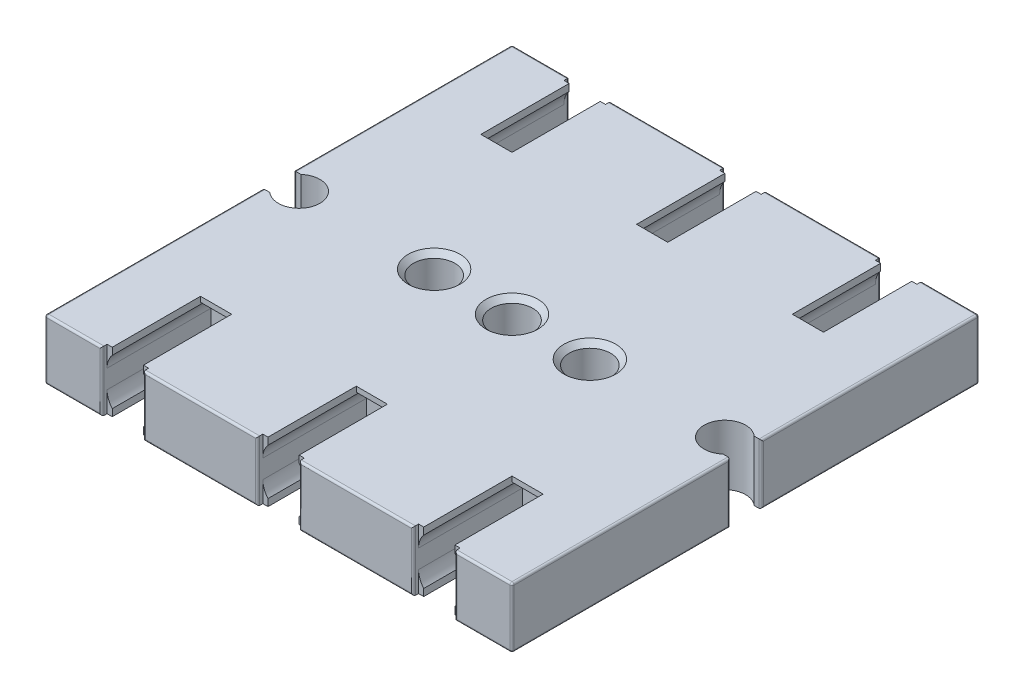
SolidWorks part; units mm, degrees
ref_plane "前视基准面" through (0, 0, 0) normal (0, 0, 1) x (1, 0, 0)
ref_plane "上视基准面" through (0, 0, 0) normal (0, 1, 0) x (1, 0, 0)
ref_plane "右视基准面" through (0, 0, 0) normal (1, 0, 0) x (0, 0, -1)
sketch "草图1" plane through (0, 0, 0) normal (0, 1, 0) x (1, 0, 0)
  line L0 (22.5, 22.5) -> (22.5, -22.5)
  line L1 (22.5, 22.5) -> (-22.5, 22.5)
  line L2 (22.5, -22.5) -> (-22.5, -22.5)
  line L3 (-22.5, 22.5) -> (-22.5, -22.5)
  line L4 (22.5, 22.5) -> (-22.5, -22.5) construction
  line L5 (22.5, -22.5) -> (-22.5, 22.5) construction
  point P1 (0, 0)
  dimension "D1" = 45
  dimension "D2" = 45
extrude "凸台-拉伸1" add sketch "草图1" along normal blind 5.8
sketch "草图2" plane through (0, 0, 22.5) normal (0, 0, 1) x (1, 0, 0)
  line L0 (-22.5, 5.8) -> (-15, 5.8) construction
  line L1 (-22.5, 5.8) -> (22.5, 5.8) construction
  line L2 (-15, 5.8) -> (-15, 3.8) construction
  line L3 (-15, 3.8) -> (-15, 2) construction
  line L4 (-15, 2) -> (-15, 0) construction
  line L5 (-22.5, 0) -> (22.5, 0) construction
  line L6 (-15, 5.8) -> (-16.5, 5.8)
  line L7 (-16.5, 5.8) -> (-16.5, 5.1229)
  line L8 (-15, 5.8) -> (-13.5, 5.8)
  line L9 (-13.5, 5.8) -> (-13.5, 5.1229)
  line L10 (-15, 3.8) -> (-17, 3.8) construction
  line L11 (-15, 3.8) -> (-13, 3.8) construction
  line L12 (-15, 0) -> (-16.5, 0)
  line L13 (-16.5, 0) -> (-16.5, 0.6771)
  line L14 (-15, 0) -> (-13.5, 0)
  line L15 (-13.5, 0) -> (-13.5, 0.6771)
  line L16 (-15, 2) -> (-17, 2) construction
  line L17 (-15, 2) -> (-13, 2) construction
  line L18 (-17, 2) -> (-17, 3.8)
  line L19 (-13, 2) -> (-13, 3.8)
  arc A0 (-13, 3.8) -> (-13.5, 5.1229) centre (-15, 3.8) ccw
  arc A1 (-16.5, 5.1229) -> (-17, 3.8) centre (-15, 3.8) ccw
  arc A2 (-13.5, 0.6771) -> (-13, 2) centre (-15, 2) ccw
  arc A3 (-17, 2) -> (-16.5, 0.6771) centre (-15, 2) ccw
  dimension "D6" = 2
  dimension "D9" = 2
  dimension "D1" = 7.5
  dimension "D2" = 2
  dimension "D3" = 1.8
  dimension "D4" = 1.5
  dimension "D5" = 1.5
  dimension "D7" = 1.5
  dimension "D8" = 1.5
extrude "切除-拉伸1" cut sketch "草图2" against normal blind 10.5
sketch "草图3" plane through (0, 0, 22.5) normal (0, 0, 1) x (1, 0, 0)
  line L0 (-22.5, 2.9) -> (-15, 2.9) construction
  line L1 (-22.5, 5.8) -> (-22.5, 0) construction
  line L2 (-17, 5.8) -> (-17, 0)
  line L3 (-17, 5.8) -> (-13, 5.8)
  line L4 (-17, 0) -> (-13, 0)
  line L5 (-13, 5.8) -> (-13, 0)
  line L6 (-17, 5.8) -> (-13, 0) construction
  line L7 (-17, 0) -> (-13, 5.8) construction
  dimension "D1" = 7.5
  dimension "D2" = 5.8
  dimension "D3" = 4
extrude "切除-拉伸2" cut sketch "草图3" against normal blind 0.5
sketch "草图4" plane through (0, 0, 12) normal (0, 0, 1) x (1, 0, 0)
  line L0 (-13.5, 5.1229) -> (-13.5, 5.8) construction
  line L1 (-16.5, 5.8) -> (-13.5, 5.8)
  line L2 (-16.5, 5.8) -> (-16.5, 5.3)
  line L3 (-16.5, 5.3) -> (-13.5, 5.3)
  line L4 (-13.5, 5.8) -> (-13.5, 5.3)
  line L5 (-13.5, 0) -> (-13.5, 0.6771) construction
  line L6 (-16.5, 0) -> (-13.5, 0)
  line L7 (-16.5, 0) -> (-16.5, 0.5)
  line L8 (-16.5, 0.5) -> (-13.5, 0.5)
  line L9 (-13.5, 0) -> (-13.5, 0.5)
  dimension "D1" = 0.5
  dimension "D2" = 0.5
extrude "凸台-拉伸2" add sketch "草图4" along normal blind 1.5
mirror "镜向1" about plane through (0, 0, 0) normal (0, 0, 1) of "切除-拉伸1", "切除-拉伸2", "凸台-拉伸2"
pattern_linear "阵列(线性)1" count 3 spacing 15 along (1, 0, 0) of "镜向1", "切除-拉伸1", "切除-拉伸2", "凸台-拉伸2"
sketch "草图5" plane through (0, 5.8, 0) normal (0, 1, 0) x (1, 0, 0)
  circle A0 centre (0, 0) radius 2
  dimension "D1" = 4
extrude "切除-拉伸3" cut sketch "草图5" against normal up to next
sketch "草图6" plane through (0, 5.8, 0) normal (0, 1, 0) x (1, 0, 0)
  line L0 (0, 0) -> (-7.5, 0) construction
  circle A0 centre (-7.5, 0) radius 2
  dimension "D2" = 4
  dimension "D1" = 7.5
extrude "切除-拉伸4" cut sketch "草图6" against normal up to next
mirror "镜向2" about plane through (0, 0, 0) normal (1, 0, 0) of "切除-拉伸4"
sketch "草图7" plane through (0, 5.8, 0) normal (0, 1, 0) x (1, 0, 0)
  line L0 (-22.5, 0) -> (-20.5, 0) construction
  line L1 (-22.5, 22.5) -> (-22.5, -22.5) construction
  line L2 (-22.5, -1.5) -> (-22.5, 1.5)
  line L3 (-22.5, 1.5) -> (-21.8229, 1.5)
  line L4 (-22.5, -1.5) -> (-21.8229, -1.5)
  arc A0 (-21.8229, -1.5) -> (-21.8229, 1.5) centre (-20.5, 0) ccw
  dimension "D3" = 2
  dimension "D1" = 2
  dimension "D2" = 1.5
extrude "切除-拉伸5" cut sketch "草图7" against normal up to next
mirror "镜向3" about plane through (0, 0, 0) normal (1, 0, 0) of "切除-拉伸5"
chamfer "倒角1" distance 0.5 angle 45 6 edges at (7.5, 0, 2) (7.5, 5.8, 2) (0, 0, 2) (0, 5.8, 2) (-7.5, 0, 2) (-7.5, 5.8, 2)
fillet "圆角1" radius 0.2 44 edges at (-22.5, 0, 12) (-22.5, 2.9, 1.5) (-22.5, 5.8, 12) (-22.5, 5.8, -12) (-22.5, 2.9, -1.5) (-22.5, 0, -12) (-19.75, 5.8, -22.5) (-22.5, 2.9, -22.5) (-19.75, 0, -22.5) (-17, 2.9, -22.5) (-7.5, 5.8, -22.5) (-13, 2.9, -22.5) (-7.5, 0, -22.5) (-2, 2.9, -22.5) (7.5, 5.8, -22.5) (2, 2.9, -22.5) (7.5, 0, -22.5) (13, 2.9, -22.5) (19.75, 0, -22.5) (19.75, 5.8, -22.5) (17, 2.9, -22.5) (22.5, 5.8, -12) (22.5, 2.9, -22.5) (22.5, 0, -12) (22.5, 2.9, -1.5) (22.5, 0, 12) (22.5, 5.8, 12) (22.5, 2.9, 1.5) (22.5, 2.9, 22.5) (19.75, 0, 22.5) (17, 2.9, 22.5) (19.75, 5.8, 22.5) (2, 2.9, 22.5) (7.5, 5.8, 22.5) (13, 2.9, 22.5) (7.5, 0, 22.5) (-13, 2.9, 22.5) (-7.5, 5.8, 22.5) (-2, 2.9, 22.5) (-7.5, 0, 22.5) (-22.5, 2.9, 22.5) (-19.75, 5.8, 22.5) (-17, 2.9, 22.5) (-19.75, 0, 22.5)
